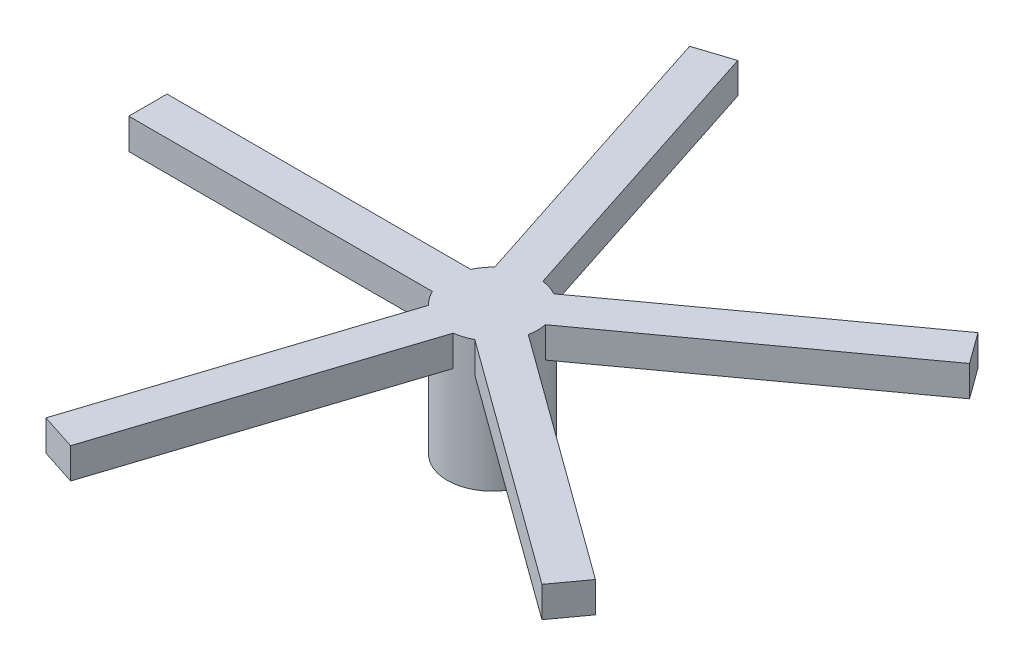
SolidWorks part; units mm, degrees
ref_plane "Front Plane" through (0, 0, 0) normal (0, 0, 1) x (1, 0, 0)
ref_plane "Top Plane" through (0, 0, 0) normal (0, 1, 0) x (1, 0, 0)
ref_plane "Right Plane" through (0, 0, 0) normal (1, 0, 0) x (0, 0, -1)
sketch "Sketch1" plane through (0, 0, 0) normal (0, 1, 0) x (1, 0, 0)
  circle A0 centre (0, 0) radius 7.493
  circle A1 centre (0, 0) radius 4.318
  dimension "D1" = 8.636
  dimension "D2" = 3.175
extrude "Boss-Extrude1" add sketch "Sketch1" along normal blind 21.59
sketch "Sketch2" plane through (0, 0, 0) normal (0, 0, 1) x (1, 0, 0)
  line L0 (4.318, 21.59) -> (-4.318, 21.59) construction
  line L1 (-57.15, 16.51) -> (0, 16.51)
  line L2 (-57.15, 16.51) -> (-57.15, 21.59)
  line L3 (-57.15, 21.59) -> (0, 21.59)
  line L4 (0, 16.51) -> (0, 21.59)
  point P6 (-57.15, 19.05)
  dimension "D1" = 19.05
  dimension "D2" = 57.15
extrude "Boss-Extrude2" add sketch "Sketch2" along normal mid plane 6.35
pattern_circular "CirPattern1" count 5 over 360 about axis through (0, 0, 0) along (0, 1, 0) of "Boss-Extrude2"
